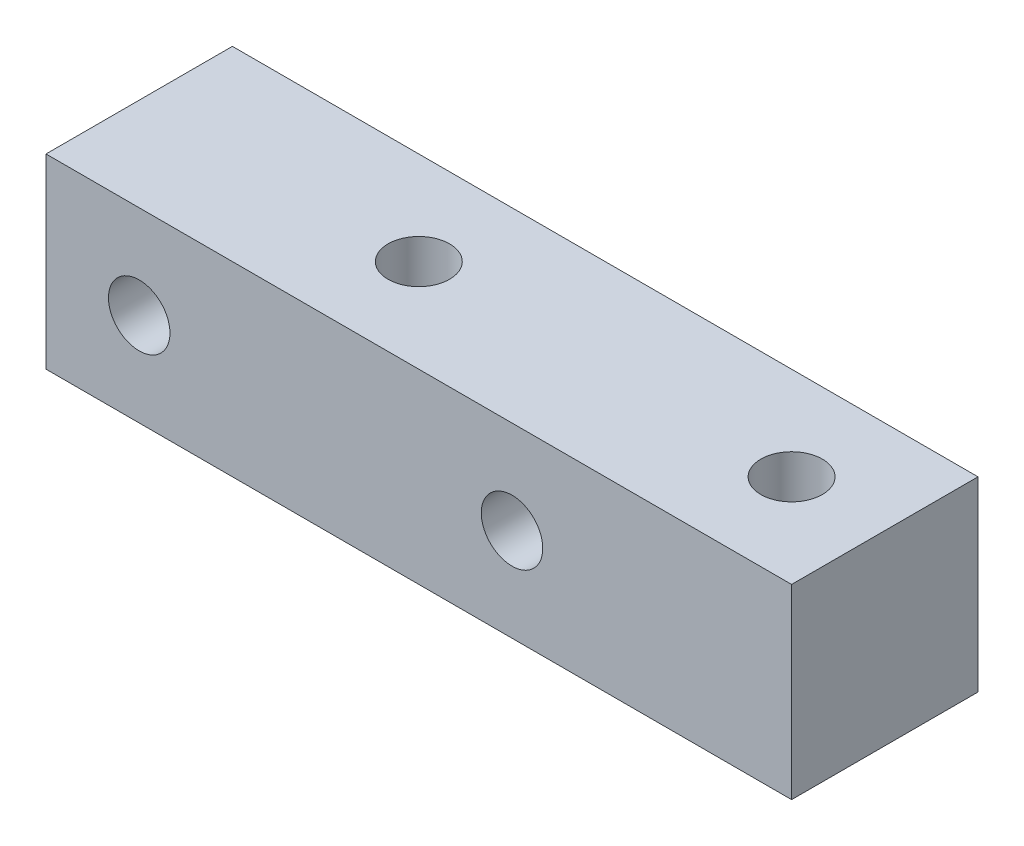
SolidWorks part; units mm, degrees
material "6061 合金"
ref_plane "前视基准面" through (0, 0, 0) normal (0, 0, 1) x (1, 0, 0)
ref_plane "上视基准面" through (0, 0, 0) normal (0, 1, 0) x (1, 0, 0)
ref_plane "右视基准面" through (0, 0, 0) normal (1, 0, 0) x (0, 0, -1)
sketch "草图1" plane through (0, 0, 0) normal (0, 0, 1) x (1, 0, 0)
  line L1 (20, -5) -> (-20, -5)
  line L2 (20, -5) -> (20, 5)
  line L3 (20, 5) -> (-20, 5)
  line L4 (-20, -5) -> (-20, 5)
  line L5 (20, -5) -> (-20, 5) construction
  line L6 (20, 5) -> (-20, -5) construction
  point P0 (0, 0)
  dimension "D1" = 40
  dimension "D2" = 10
extrude "凸台-拉伸1" add sketch "草图1" along normal blind 10
sketch "草图2" plane through (0, 0, 10) normal (0, 0, 1) x (1, 0, 0)
  line L0 (-20, 5) -> (-20, -5) construction
  point P0 (5, 0)
  point P1 (-15, 0)
  dimension "D1" = 5
  dimension "D2" = 20
sketch "草图3" plane through (0, 5, 0) normal (0, 1, 0) x (1, 0, 0)
  line L0 (20, -10) -> (20, 0) construction
  point P0 (15, -5)
  point P1 (-5, -5)
  dimension "D1" = 5
  dimension "D2" = 20
hole_wizard "M4 螺纹孔的螺纹孔钻头1" positions "3D草图1" profile "草图4" hole size "M4" standard "DIN" end condition through all
sketch3d "3D草图1"
  point P0 (-5, 5, 5)
  point P3 (15, 5, 5)
  point P6 (5, 0, 10)
  point P9 (-15, 0, 10)
  point P12 (-15, 0, 10)
sketch "草图4" plane through (-5, 5, 5) normal (1, 0, 0) x (0, 0, 1)
  line L0 (0, 0) -> (0, 10)
  line L1 (0, 10) -> (1.65, 10)
  line L2 (1.65, 10) -> (1.65, 0)
  line L5 (1.65, 0) -> (0, 0)
  line L11 (0, -6.35) -> (0, 107.95) construction
  dimension "通孔孔直径" = 3.3
  dimension "通孔孔深度" = 10
